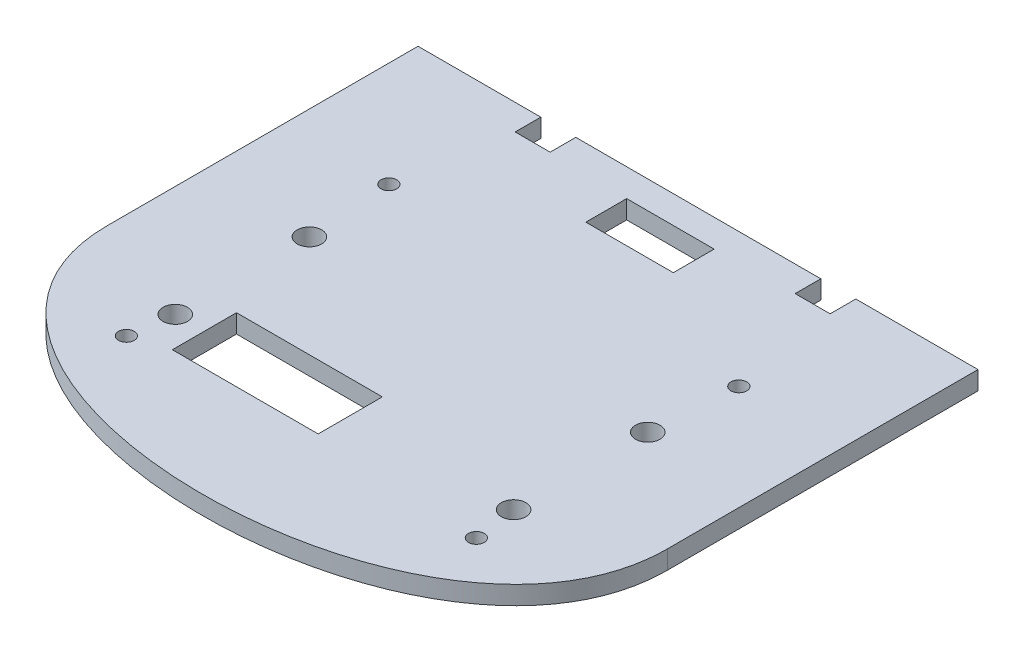
SolidWorks part; units mm, degrees
ref_plane "Front Plane" through (0, 0, 0) normal (0, 0, 1) x (1, 0, 0)
ref_plane "Top Plane" through (0, 0, 0) normal (0, 1, 0) x (1, 0, 0)
ref_plane "Right Plane" through (0, 0, 0) normal (1, 0, 0) x (0, 0, -1)
sketch "Sketch2" plane through (0, 0, 0) normal (0, 1, 0) x (1, 0, 0)
  line L4 (-48, -33.6908) -> (-48, 91.0268) construction
  line L5 (48, -42.5) -> (-48, -42.5) construction
  line L6 (48, -42.5) -> (48, 42.5) construction
  line L7 (48, 42.5) -> (-48, 42.5)
  line L8 (-48, -42.5) -> (-48, 42.5) construction
  line L9 (48, -42.5) -> (-48, 42.5) construction
  line L10 (48, 42.5) -> (-48, -42.5) construction
  line L11 (48, 148.5724) -> (48, -105.4276) construction
  line L12 (-48, 42.5) -> (-48, -10.75)
  line L13 (48, 42.5) -> (48, -10.75)
  spline S0 degree 3 poles (-48, -10.75) (-48, -53.0833) (48, -53.0833) (48, -10.75) knots 0 0 0 0 1 1 1 1
  point P0 (0, 0)
  dimension "D3" = 180
  dimension "D4" = 127
  dimension "D5" = 85
  dimension "D1" = 96
  dimension "D2" = 180
  dimension "D6" = 127
extrude "Boss-Extrude1" add sketch "Sketch2" along normal blind 3.175
sketch "Sketch3" plane through (0, 3.175, 0) normal (0, 1, 0) x (1, 0, 0)
  line L0 (0, 0) -> (0, 43.6246) construction
  line L9 (-29, 4.8813) -> (29, 4.8813) construction
  line L10 (48, 42.5) -> (-48, 42.5) construction
  line L11 (-7.5, 37.765) -> (7.5, 37.765)
  line L12 (-24, -12.6187) -> (1, -12.6187)
  line L13 (-30, 19.5) -> (-30, -25.5) construction
  line L14 (30, 19.5) -> (30, -25.5) construction
  line L15 (0, -42.5) -> (29.21, -42.5) construction
  line L16 (-24, -12.6187) -> (-24, -23.6187)
  line L17 (-24, -23.6187) -> (1, -23.6187)
  line L18 (1, -12.6187) -> (1, -23.6187)
  line L19 (-24, -12.6187) -> (1, -23.6187) construction
  line L20 (-24, -23.6187) -> (1, -12.6187) construction
  line L21 (-7.5, 37.765) -> (-7.5, 30.765)
  line L22 (-7.5, 30.765) -> (7.5, 30.765)
  line L23 (7.5, 37.765) -> (7.5, 30.765)
  line L24 (-7.5, 37.765) -> (7.5, 30.765) construction
  line L25 (-7.5, 30.765) -> (7.5, 37.765) construction
  circle A2 centre (-30, 19.5) radius 1.35
  circle A5 centre (-30, -25.5) radius 1.35
  circle A6 centre (30, -25.5) radius 1.35
  circle A7 centre (30, 19.5) radius 1.35
  circle A8 centre (-29, 4.8813) radius 2.1
  circle A9 centre (-29, -18.1187) radius 2.1
  circle A10 centre (29, -18.1187) radius 2.1
  circle A11 centre (29, 4.8813) radius 2.1
  spline S0 degree 3 poles (-48, -10.75) (-48, -53.0833) (48, -53.0833) (48, -10.75) knots 0 0 0 0 1 1 1 1 construction
  point P0 (-11.5, -18.1187)
  point P9 (0, 34.265)
  point P35 (0, 0)
  point P36 (0, 4.8813)
  point P37 (-11.5, -17.2535)
  point P38 (0, 0)
  point P39 (-29, 4.3492)
  dimension "D5" = 15
  dimension "D6" = 7
  dimension "D9" = 2.7
  dimension "D13" = 23
  dimension "D2" = 25
  dimension "D7" = 58
  dimension "D8" = 23
  dimension "D14" = 58
  dimension "D4" = 5
  dimension "D3" = 11
  dimension "D10" = 23
  dimension "D11" = 30
  dimension "D12" = 45
extrude "Cut-Extrude1" cut sketch "Sketch3" against normal through all and the other way through all
sketch "Sketch5" plane through (0, 3.175, 0) normal (0, 1, 0) x (1, 0, 0)
  line L0 (0.0511, -12) -> (0.0511, 44.8666) construction
  line L1 (48, 42.5) -> (-48, 42.5) construction
  line L10 (27.0511, 42.5) -> (27.0511, 38.1)
  line L11 (21.0511, 42.5) -> (27.0511, 42.5)
  line L12 (21.0511, 38.1) -> (27.0511, 38.1)
  line L13 (21.0511, 42.5) -> (21.0511, 38.1)
  line L18 (-20.9489, 42.5) -> (-20.9489, 38.1)
  line L19 (-26.9489, 42.5) -> (-20.9489, 42.5)
  line L20 (-26.9489, 38.1) -> (-20.9489, 38.1)
  line L21 (-26.9489, 42.5) -> (-26.9489, 38.1)
  point P2 (-20.9489, 40.3)
  dimension "D1" = 6
  dimension "D2" = 6
  dimension "D3" = 4.4
  dimension "D4" = 4.4
extrude "Cut-Extrude2" cut sketch "Sketch5" against normal through all
